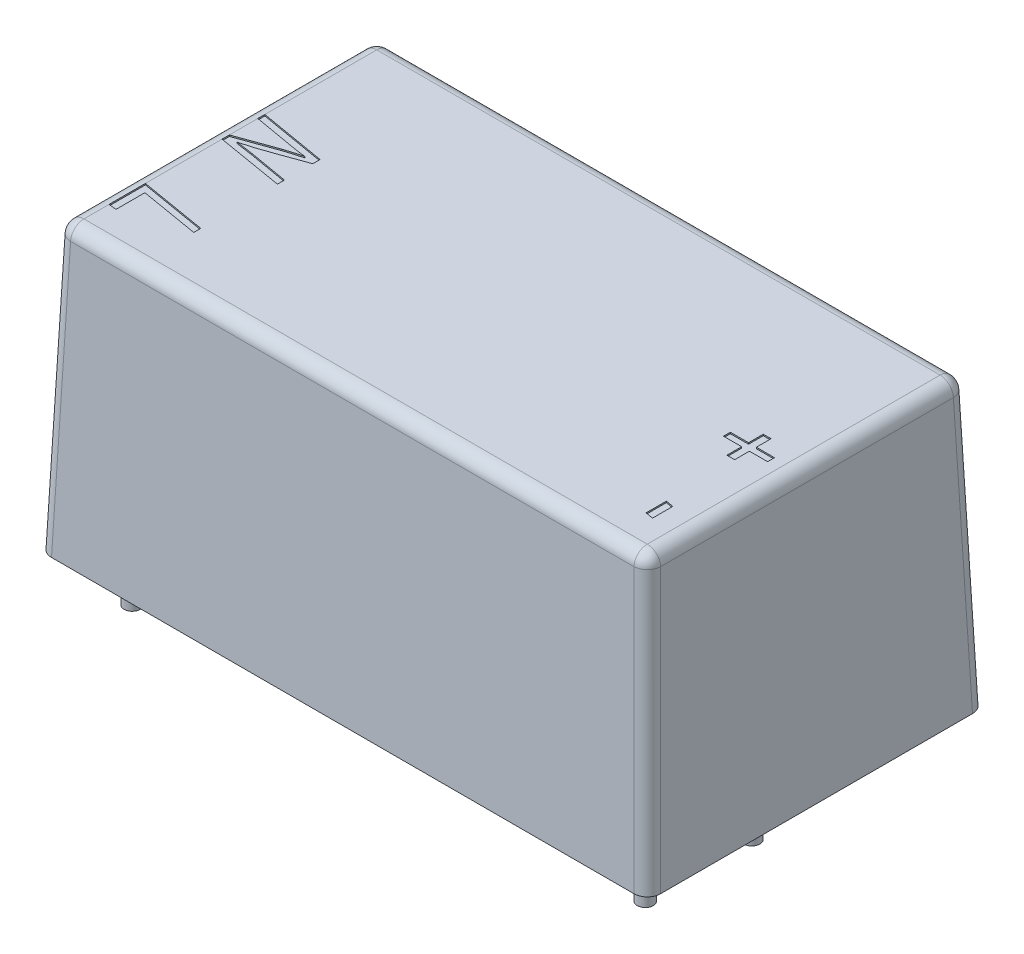
SolidWorks part; units mm, degrees
ref_plane "Спереди" through (0, 0, 0) normal (0, 0, 1) x (1, 0, 0)
ref_plane "Сверху" through (0, 0, 0) normal (0, 1, 0) x (1, 0, 0)
ref_plane "Справа" through (0, 0, 0) normal (1, 0, 0) x (0, 0, -1)
sketch "Эскиз1" plane through (0, 0, 0) normal (0, 1, 0) x (1, 0, 0)
  line L1 (-22.85, 12.7) -> (22.85, 12.7)
  line L2 (-22.85, 12.7) -> (-22.85, -12.7)
  line L3 (-22.85, -12.7) -> (22.85, -12.7)
  line L4 (22.85, 12.7) -> (22.85, -12.7)
  line L5 (-22.85, 12.7) -> (22.85, -12.7) construction
  line L6 (-22.85, -12.7) -> (22.85, 12.7) construction
  point P0 (0, 0)
extrude "Бобышка-Вытянуть1" add sketch "Эскиз1" along normal blind 21.5 draft 2
fillet "Скругление1" radius 1 8 edges at (22.0992, 21.5, 0) (0, 21.5, -11.9492) (-22.0992, 21.5, 0) (22.4746, 10.75, 12.3246) (-22.4746, 10.75, 12.3246) (-22.4746, 10.75, -12.3246) (22.4746, 10.75, -12.3246) (0, 21.5, 11.9492)
sketch "Эскиз2" plane through (0, 0, 0) normal (0, -1, 0) x (1, 0, 0)
  line L0 (0, 0) -> (0, 15.7574) construction
  line L2 (-21.8506, 12.7) -> (21.8506, 12.7) construction
  circle A0 centre (-19.25, 9.25) radius 0.6
  circle A1 centre (19.25, 9.25) radius 0.6
  circle A2 centre (19.25, 1.25) radius 0.6
  circle A3 centre (-19.25, -1.5) radius 0.6
  point P11 (0, 0)
  point P12 (0, 0)
  point P13 (0, 0)
  point P16 (0, 0)
  dimension "D1" = 38.5
  dimension "D2" = 3.45
  dimension "D3" = 10.75
  dimension "D4" = 8
extrude "Бобышка-Вытянуть2" add sketch "Эскиз2" along normal blind 3.5
sketch "Эскиз3" plane through (0, 21.5, 0) normal (0, 1, 0) x (1, 0, 0)
  line L0 (21.1335, 9.416) -> (21.1335, -10.9835) construction
  line L1 (-21.1335, 10.9835) -> (-21.1335, -10.9835) construction
  text T0 "<i> -   +</i>" font "Arial Narrow" height 5
  text T1 "N   L " font "Arial Narrow" height 5
extrude "Вырез-Вытянуть1" cut sketch "Эскиз3" against normal blind 0.1
